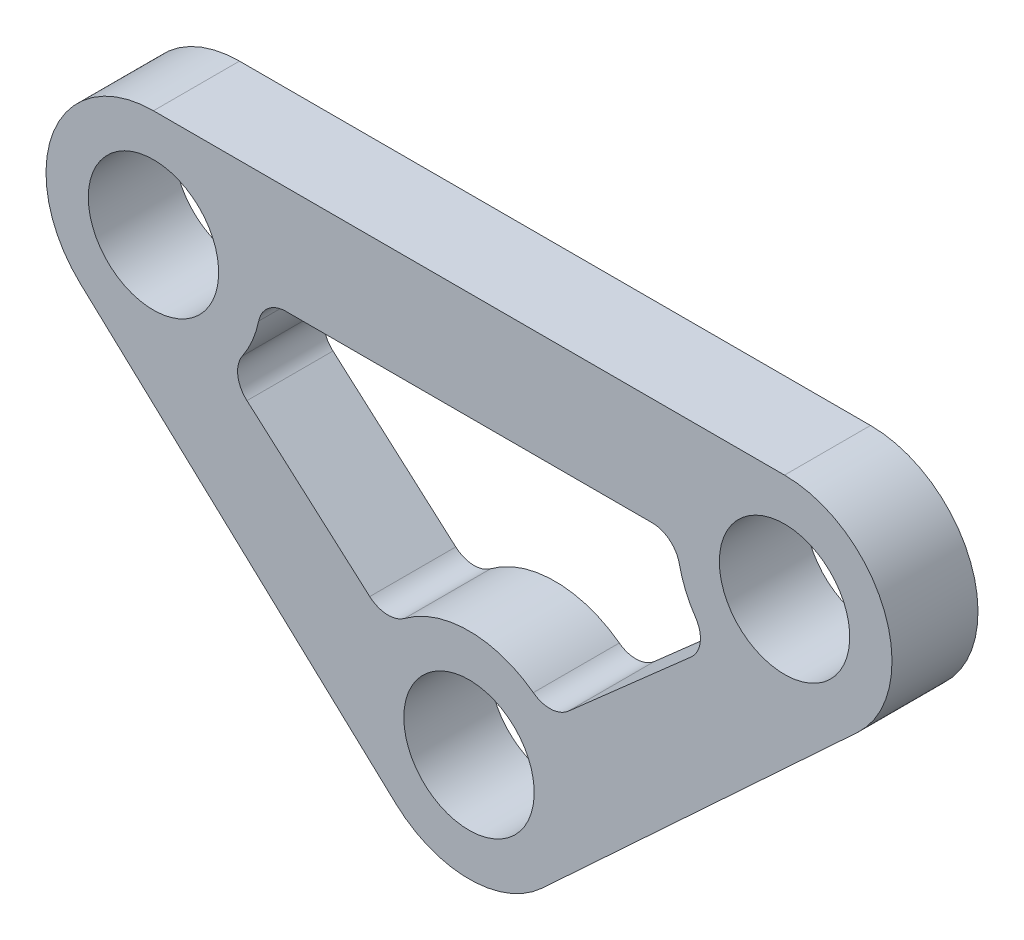
SolidWorks part; units mm, degrees
ref_plane "Front Plane" through (0, 0, 0) normal (0, 0, 1) x (1, 0, 0)
ref_plane "Top Plane" through (0, 0, 0) normal (0, 1, 0) x (1, 0, 0)
ref_plane "Right Plane" through (0, 0, 0) normal (1, 0, 0) x (0, 0, -1)
sketch "Sketch1" plane through (0, 0, 0) normal (0, 0, 1) x (1, 0, 0)
  line L0 (-37.1382, 29.9335) -> (-14.3882, 29.9335)
  line L1 (-25.7632, 26.0585) -> (-25.7632, 19.3835) construction
  line L5 (-33.7675, 22.5686) -> (-29.3415, 18.6647)
  line L6 (-17.7588, 22.5686) -> (-22.1849, 18.6647)
  line L12 (-32.3668, 26.0585) -> (-19.1595, 26.0585)
  line L15 (-11.7531, 23.2174) -> (-23.1281, 12.6674)
  line L16 (-39.7732, 23.2174) -> (-28.3982, 12.6674)
  circle A0 centre (-14.3882, 26.0585) radius 2.35
  circle A1 centre (-37.1382, 26.0585) radius 2.35
  circle A2 centre (-25.7632, 15.5085) radius 2.35
  arc A4 (-11.7531, 23.2174) -> (-14.3882, 29.9335) centre (-14.3882, 26.0585) ccw
  arc A5 (-28.3982, 12.6674) -> (-23.1281, 12.6674) centre (-25.7632, 15.5085) ccw
  arc A7 (-17.5932, 23.8806) -> (-18.1808, 25.2636) centre (-14.3882, 26.0585) cw
  arc A8 (-23.4447, 18.6134) -> (-28.0817, 18.6134) centre (-25.7632, 15.5085) ccw
  arc A9 (-32.3668, 26.0585) -> (-33.3456, 25.2636) centre (-32.3668, 25.0585) ccw
  arc A10 (-33.9331, 23.8806) -> (-33.7675, 22.5686) centre (-33.106, 23.3185) ccw
  arc A11 (-28.0817, 18.6134) -> (-29.3415, 18.6647) centre (-28.68, 19.4146) cw
  arc A12 (-22.1849, 18.6647) -> (-23.4447, 18.6134) centre (-22.8463, 19.4146) cw
  arc A13 (-17.5932, 23.8806) -> (-17.7588, 22.5686) centre (-18.4203, 23.3185) cw
  arc A14 (-19.1595, 26.0585) -> (-18.1808, 25.2636) centre (-19.1595, 25.0585) cw
  arc A15 (-37.1382, 29.9335) -> (-39.7732, 23.2174) centre (-37.1382, 26.0585) ccw
  arc A16 (-33.9331, 23.8806) -> (-33.3456, 25.2636) centre (-37.1382, 26.0585) ccw
  dimension "D6" = 1
  dimension "D7" = 4.7
  dimension "D8" = 4.7
  dimension "D9" = 15.5143
  dimension "D11" = 3.875
  dimension "D10" = 5.9017
extrude "Extrude1" add sketch "Sketch1" along normal blind 3.1
